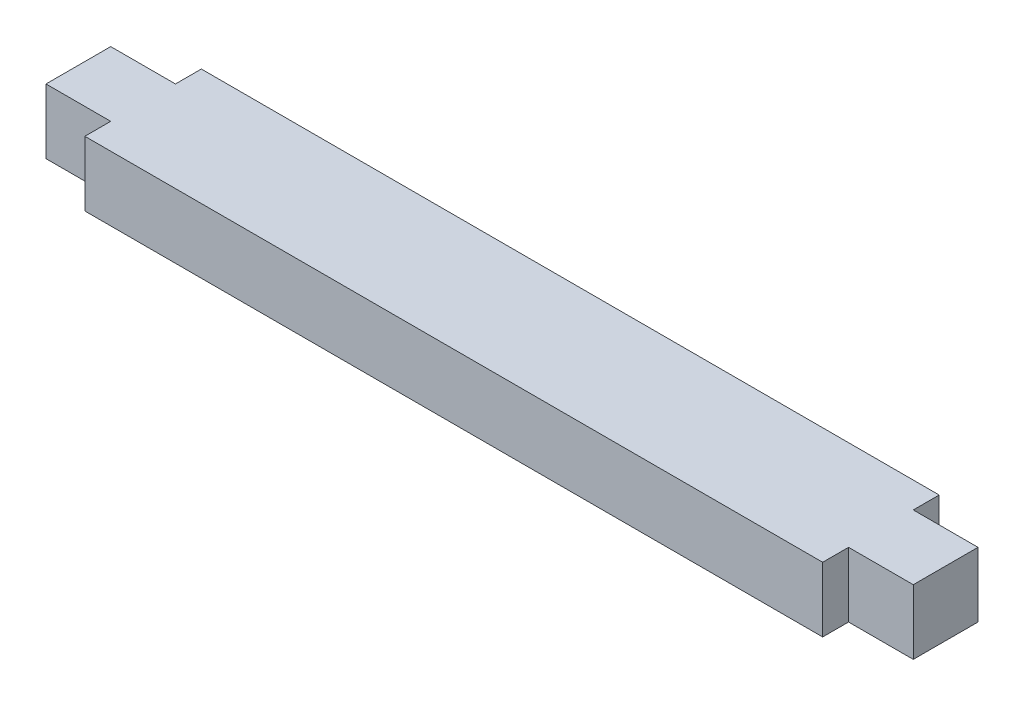
SolidWorks part; units mm, degrees
ref_plane "Front Plane" through (0, 0, 0) normal (0, 0, 1) x (1, 0, 0)
ref_plane "Top Plane" through (0, 0, 0) normal (0, 1, 0) x (1, 0, 0)
ref_plane "Right Plane" through (0, 0, 0) normal (1, 0, 0) x (0, 0, -1)
sketch "Sketch1" plane through (0, 0, 0) normal (0, 1, 0) x (1, 0, 0)
  line L0 (-50.8, 0) -> (88.3482, 0) construction
  line L1 (-36.195, 5.715) -> (36.195, 5.715)
  line L2 (-36.195, 5.715) -> (-36.195, 3.175)
  line L3 (-36.195, -5.715) -> (36.195, -5.715)
  line L4 (36.195, 5.715) -> (36.195, 3.175)
  line L5 (-36.195, 5.715) -> (36.195, -5.715) construction
  line L6 (-36.195, -5.715) -> (36.195, 5.715) construction
  line L7 (36.195, -3.175) -> (36.195, -5.715)
  line L8 (36.195, 3.175) -> (42.545, 3.175)
  line L9 (0, 5.715) -> (0, -5.715) construction
  line L10 (36.195, -3.175) -> (42.545, -3.175)
  line L11 (42.545, 3.175) -> (42.545, -3.175)
  line L12 (36.195, 3.175) -> (42.545, -3.175) construction
  line L13 (36.195, -3.175) -> (42.545, 3.175) construction
  line L14 (-36.195, -3.175) -> (-42.545, -3.175)
  line L15 (-42.545, 3.175) -> (-42.545, -3.175)
  line L16 (-36.195, 3.175) -> (-42.545, 3.175)
  line L17 (-36.195, -3.175) -> (-36.195, -5.715)
  point P0 (0, 0)
  point P8 (39.37, 0)
  dimension "D1" = 6.35
  dimension "D2" = 72.39
  dimension "D3" = 2.54
extrude "Boss-Extrude1" add sketch "Sketch1" along normal blind 6.35
